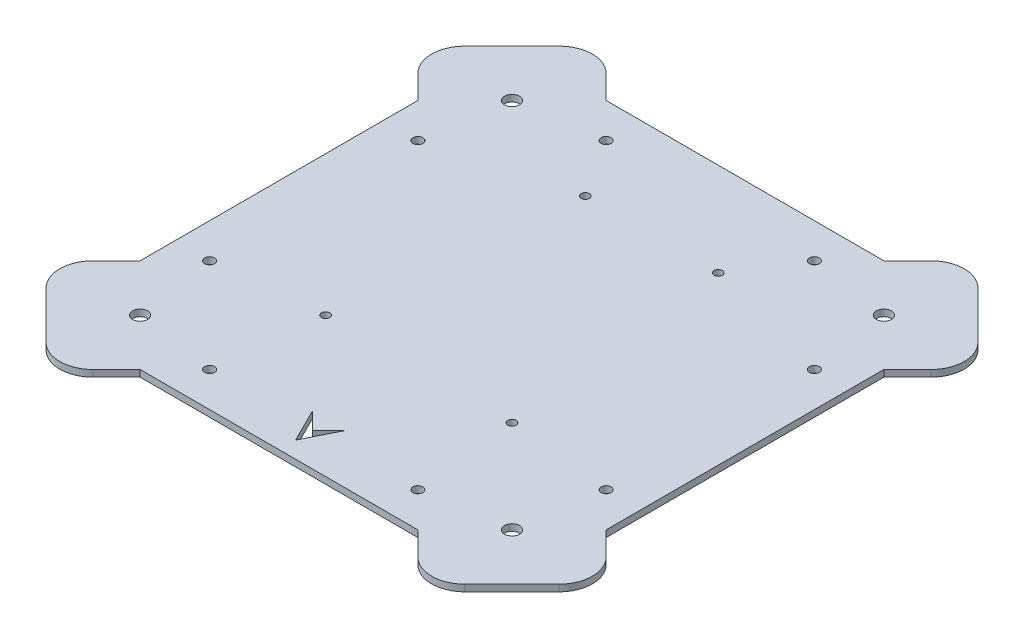
SolidWorks part; units mm, degrees
ref_plane "Front Plane" through (0, 0, 0) normal (0, 0, 1) x (1, 0, 0)
ref_plane "Top Plane" through (0, 0, 0) normal (0, 1, 0) x (1, 0, 0)
ref_plane "Right Plane" through (0, 0, 0) normal (1, 0, 0) x (0, 0, -1)
sketch "Sketch1" plane through (0, 0, 0) normal (0, 1, 0) x (1, 0, 0)
  line L1 (0, 0) -> (140, 0)
  line L2 (0, 0) -> (0, 140)
  line L3 (0, 140) -> (140, 140)
  line L4 (140, 0) -> (140, 140)
  dimension "D1" = 140
  dimension "D2" = 140
extrude "Boss-Extrude1" add sketch "Sketch1" along normal blind 2
sketch "Sketch2" plane through (0, 2, 0) normal (0, 1, 0) x (1, 0, 0)
  line L0 (70, 140) -> (70, 0) construction
  line L1 (140, 140) -> (0, 140) construction
  line L2 (0, 0) -> (140, 0) construction
  line L3 (140, 70) -> (0, 70) construction
  line L4 (140, 0) -> (140, 140) construction
  line L5 (0, 140) -> (0, 0) construction
  line L6 (70, 70) -> (140, 140) construction
  line L7 (125.8579, 125.8579) -> (140, 111.7157) construction
  line L8 (125.8579, 125.8579) -> (111.7157, 140) construction
  line L9 (111.7157, 140) -> (140, 111.7157)
  line L10 (111.7157, 140) -> (125.8579, 154.1421)
  line L11 (140, 111.7157) -> (154.1421, 125.8579)
  line L12 (125.8579, 154.1421) -> (154.1421, 125.8579)
  line L13 (0, 111.7157) -> (-14.1421, 125.8579)
  line L14 (14.1421, 154.1421) -> (-14.1421, 125.8579)
  line L15 (28.2843, 140) -> (14.1421, 154.1421)
  line L16 (28.2843, 140) -> (0, 111.7157)
  line L17 (28.2843, 0) -> (0, 28.2843)
  line L18 (28.2843, 0) -> (14.1421, -14.1421)
  line L19 (14.1421, -14.1421) -> (-14.1421, 14.1421)
  line L20 (0, 28.2843) -> (-14.1421, 14.1421)
  line L21 (140, 28.2843) -> (154.1421, 14.1421)
  line L22 (125.8579, -14.1421) -> (154.1421, 14.1421)
  line L23 (111.7157, 0) -> (125.8579, -14.1421)
  line L24 (111.7157, 0) -> (140, 28.2843)
  point P33 (140, 111.7157)
  point P34 (111.7157, 140)
  dimension "D1" = 40
  dimension "D2" = 20
extrude "Boss-Extrude3" add sketch "Sketch2" against normal blind 2
fillet "Fillet1" radius 10 8 edges at (154.1421, 1, -14.1421) (125.8579, 1, 14.1421) (14.1421, 1, 14.1421) (-14.1421, 1, -14.1421) (-14.1421, 1, -125.8579) (14.1421, 1, -154.1421) (125.8579, 1, -154.1421) (154.1421, 1, -125.8579)
sketch "Sketch4" plane through (0, 2, 0) normal (0, 1, 0) x (1, 0, 0)
  line L0 (70, 140) -> (70, 0) construction
  line L1 (111.7157, 140) -> (28.2843, 140) construction
  line L2 (28.2843, 0) -> (111.7157, 0) construction
  line L3 (0, 70) -> (140, 70) construction
  line L4 (0, 111.7157) -> (0, 28.2843) construction
  line L5 (140, 28.2843) -> (140, 111.7157) construction
  line L6 (28.2843, 0) -> (70, 41.7157) construction
  line L7 (35.0089, 35.0089) -> (6.7246, 6.7246) construction
  circle A0 centre (38.7176, 10.4334) radius 1.5
  circle A1 centre (10.4334, 38.7176) radius 1.5
  circle A2 centre (101.2824, 10.4334) radius 1.5
  circle A3 centre (129.5666, 38.7176) radius 1.5
  circle A4 centre (38.7176, 129.5666) radius 1.5
  circle A5 centre (10.4334, 101.2824) radius 1.5
  circle A6 centre (101.2824, 129.5666) radius 1.5
  circle A7 centre (129.5666, 101.2824) radius 1.5
  dimension "D1" = 3
  dimension "D2" = 10.4334
extrude "Cut-Extrude2" cut sketch "Sketch4" against normal blind 2
sketch "Sketch5" plane through (0, 2, 0) normal (0, 1, 0) x (1, 0, 0)
  line L0 (0, 28.2843) -> (28.2843, 0) construction
  line L1 (70, 140) -> (70, 0) construction
  line L2 (111.7157, 140) -> (28.2843, 140) construction
  line L3 (28.2843, 0) -> (111.7157, 0) construction
  line L4 (0, 70) -> (140, 70) construction
  line L5 (0, 111.7157) -> (0, 28.2843) construction
  line L6 (140, 28.2843) -> (140, 111.7157) construction
  circle A0 centre (14.1421, 14.1421) radius 2.25
  circle A1 centre (125.8579, 14.1421) radius 2.25
  circle A2 centre (14.1421, 125.8579) radius 2.25
  circle A3 centre (125.8579, 125.8579) radius 2.25
  dimension "D1" = 4.5
extrude "Cut-Extrude3" cut sketch "Sketch5" against normal blind 10
sketch "Sketch6" plane through (0, 2, 0) normal (0, 1, 0) x (1, 0, 0)
  line L0 (70, 140) -> (70, 0) construction
  line L1 (111.7157, 140) -> (28.2843, 140) construction
  line L2 (28.2843, 0) -> (111.7157, 0) construction
  line L3 (0, 70) -> (140, 70) construction
  line L4 (0, 111.7157) -> (0, 28.2843) construction
  line L5 (140, 28.2843) -> (140, 111.7157) construction
  line L6 (70, 112) -> (90, 112) construction
  line L7 (70, 42) -> (98, 42) construction
  circle A0 centre (90, 112) radius 1.25
  circle A1 centre (98, 42) radius 1.25
  circle A2 centre (42, 42) radius 1.25
  circle A3 centre (50, 112) radius 1.25
  point P22 (70, 70)
  dimension "D1" = 2.5
  dimension "D2" = 40
  dimension "D4" = 56
  dimension "D3" = 70
  dimension "D5" = 39.598
extrude "Cut-Extrude4" cut sketch "Sketch6" against normal blind 15
sketch "Sketch7" plane through (0, 2, 0) normal (0, 1, 0) x (1, 0, 0)
  line L0 (70, 0) -> (70, 140) construction
  line L1 (28.2843, 0) -> (111.7157, 0) construction
  line L2 (111.7157, 140) -> (28.2843, 140) construction
  line L3 (70, 15) -> (75, 15) construction
  line L4 (75, 15) -> (70, 5)
  line L5 (70, 10) -> (75, 15)
  line L6 (65, 15) -> (70, 5)
  line L7 (70, 10) -> (65, 15)
  point P8 (70, 5)
  point P9 (70, 10)
  dimension "D1" = 5
  dimension "D2" = 10
  dimension "D3" = 5
  dimension "D4" = 5
extrude "Cut-Extrude5" cut sketch "Sketch7" against normal blind 2
